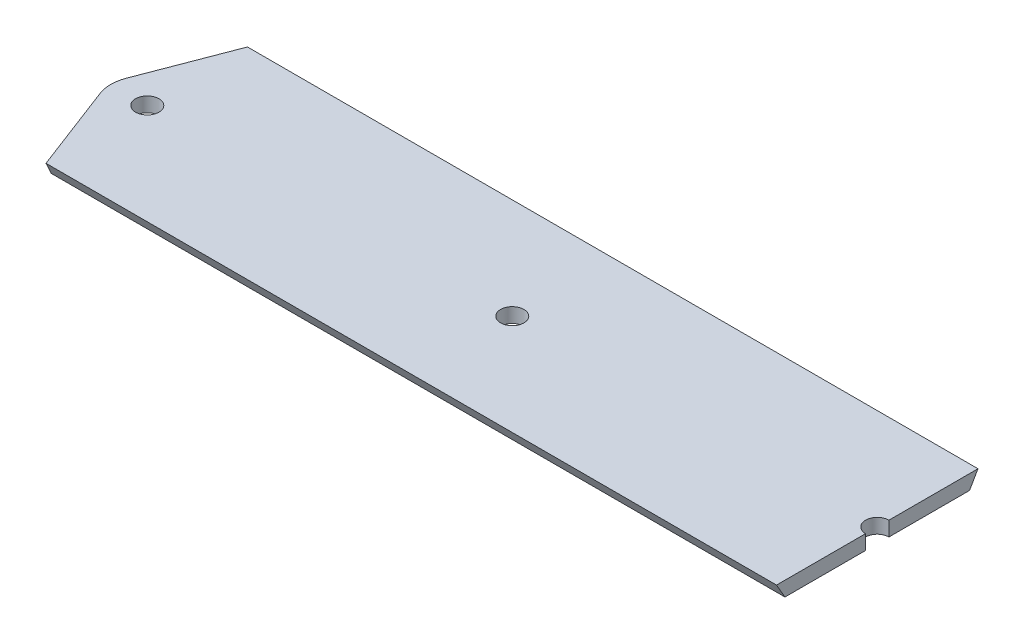
SolidWorks part; units mm, degrees
material "Медь"
ref_plane "Front" through (0, 0, 0) normal (0, 0, 1) x (1, 0, 0)
ref_plane "Top" through (0, 0, 0) normal (0, 1, 0) x (1, 0, 0)
ref_plane "Right" through (0, 0, 0) normal (1, 0, 0) x (0, 0, -1)
sketch "Эскиз1" plane through (0, 0, 0) normal (0, 1, 0) x (1, 0, 0)
  line L0 (-50, 14) -> (-54.6702, 1.7857)
  line L1 (50, -14) -> (-50, -14)
  line L2 (-50, 14) -> (-50, -14) construction
  line L3 (50, 14) -> (-50, 14)
  line L4 (50, -14) -> (50, -1.6)
  line L5 (50, -14) -> (-50, 14) construction
  line L6 (50, 14) -> (-50, -14) construction
  line L7 (-54.6702, -1.7857) -> (-50, -14)
  line L8 (0, 0) -> (0, 14) construction
  line L12 (50, 1.6) -> (50, 14)
  circle A0 centre (-50, 0) radius 1.6
  arc A1 (-54.6702, 1.7857) -> (-54.6702, -1.7857) centre (-50, 0) ccw
  circle A2 centre (0, 0) radius 1.6
  arc A3 (50, -1.6) -> (50, 1.6) centre (50, 0) cw
  point P0 (0, 0)
  dimension "D3" = 3.2
  dimension "D4" = 10
  dimension "D1" = 100
  dimension "D2" = 28
extrude "Бобышка-Вытянуть1" add sketch "Эскиз1" along normal blind 2 contours L4 A3 L12 L3 L0 A1 L7 L1 A0 A2
ref_plane "Плоскость1" through (-55, 0, 0) normal (-1, 0, 0) x (0, 0, 1)
sketch "Эскиз2" plane through (-55, 0, 0) normal (-1, 0, 0) x (0, 0, 1)
  line L0 (0, 0) -> (0, 2) construction
  line L2 (-14, 0) -> (-12.6453, 0)
  line L4 (-12.6453, 0) -> (-13.8, 2)
  line L6 (-13.8, 2) -> (-14, 2)
  line L7 (-14, 2) -> (-14, 0)
  line L8 (14, 2) -> (14, 0)
  line L9 (13.8, 2) -> (14, 2)
  line L10 (12.6453, 0) -> (13.8, 2)
  line L11 (14, 0) -> (12.6453, 0)
  line L12 (-14, 2) -> (-14, 0) construction
  line L13 (-14, 0) -> (-1.7857, 0) construction
  line L14 (-14, 2) -> (-1.7857, 2) construction
  line L15 (1.7857, 2) -> (-1.7857, 2) construction
  dimension "D1" = 0.2
  dimension "D2" = 120
extrude "Вырез-Вытянуть1" cut sketch "Эскиз2" against normal through all
